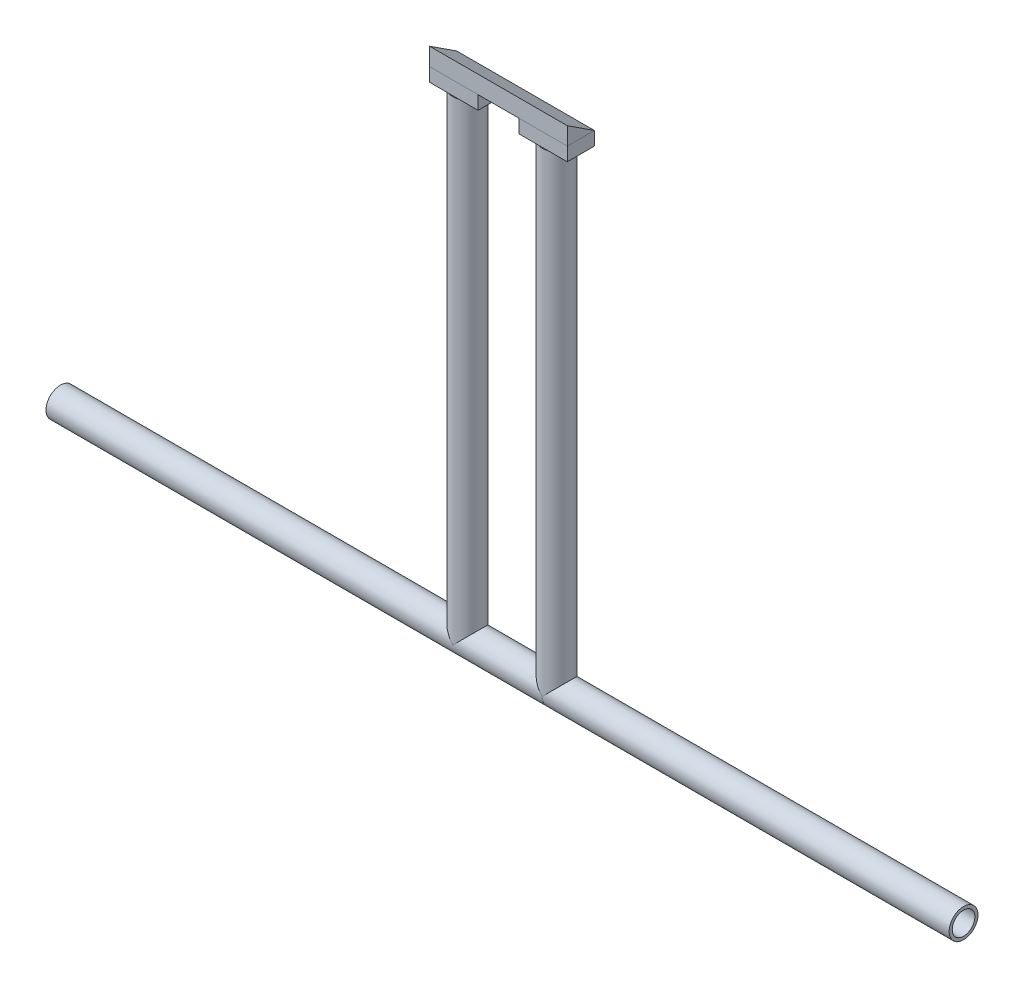
SolidWorks part; units mm, degrees
material "Hexcel AS4C (3000 Filaments)"
ref_plane "Front Plane" through (0, 0, 0) normal (0, 0, 1) x (1, 0, 0)
ref_plane "Top Plane" through (0, 0, 0) normal (0, 1, 0) x (1, 0, 0)
ref_plane "Right Plane" through (0, 0, 0) normal (1, 0, 0) x (0, 0, -1)
sketch "Sketch1" plane through (0, 0, 0) normal (0, 0, 1) x (1, 0, 0)
  line L0 (0, 350) -> (0, 0)
  line L1 (0, 0) -> (-365.75, 0)
  line L2 (0, 0) -> (300, 0)
  line L3 (-65.75, 0) -> (-65.75, 350)
  dimension "D1" = 350
  dimension "D2" = 65.75
  dimension "D3" = 300
  dimension "D4" = 300
other "Pipe - configured 21.3 X 2.3(1)"
ref_plane "Plane1" through (-65.75, 0, 0) normal (0, 1, 0) x (-1, 0, 0)
sketch "Sketch12" plane through (-65.75, 0, 0) normal (0, 1, 0) x (-1, 0, 0)
  circle A0 centre (0, 0) radius 8.35
  circle A1 centre (0, 0) radius 10.65
  point P3 (0, 10.65)
  point P5 (-10.65, 0)
  point P6 (0, -10.65)
  point P7 (10.65, 0)
  point P8 (0, 0)
  dimension "In_dia" = 16.7
  dimension "Out_dia" = 21.3
other "Pipe - configured 21.3 X 2.3(2)"
ref_plane "Plane2" through (0, 0, 0) normal (-1, 0, 0) x (0, -1, 0)
sketch "Sketch13" plane through (0, 0, 0) normal (-1, 0, 0) x (0, -1, 0)
  circle A0 centre (0, 0) radius 8.35
  circle A1 centre (0, 0) radius 10.65
  point P3 (0, 10.65)
  point P5 (-10.65, 0)
  point P6 (0, -10.65)
  point P7 (10.65, 0)
  point P8 (0, 0)
  dimension "In_dia" = 16.7
  dimension "Out_dia" = 21.3
ref_plane "Plane3" through (0, 350, 0) normal (0, 1, 0) x (1, 0, 0)
sketch "Sketch15" plane through (0, 350, 0) normal (0, 1, 0) x (1, 0, 0)
  line L1 (-83.625, 10) -> (-47.875, 10)
  line L2 (-83.625, 10) -> (-83.625, -10)
  line L3 (-83.625, -10) -> (-47.875, -10)
  line L4 (-47.875, 10) -> (-47.875, -10)
  line L5 (-83.625, 10) -> (-47.875, -10) construction
  line L6 (-83.625, -10) -> (-47.875, 10) construction
  line L7 (-17.875, 10) -> (17.875, 10)
  line L8 (-17.875, 10) -> (-17.875, -10)
  line L9 (-17.875, -10) -> (17.875, -10)
  line L10 (17.875, 10) -> (17.875, -10)
  line L11 (-17.875, 10) -> (17.875, -10) construction
  line L12 (-17.875, -10) -> (17.875, 10) construction
  point P0 (-65.75, 0)
  point P6 (0, 0)
  dimension "D1" = 35.75
  dimension "D2" = 20
  dimension "D3" = 20
  dimension "D4" = 35.75
extrude "Boss-Extrude3" add sketch "Sketch15" along normal blind 10 separate body
sketch "Sketch16" plane through (-83.625, 0, 0) normal (-1, 0, 0) x (0, 0, 1)
  line L0 (10, 360) -> (10, 373.0364)
  line L1 (-10, 360) -> (10, 360) construction
  line L2 (10, 373.0364) -> (-10, 360)
  line L3 (-10, 360) -> (-10, 350) construction
  line L4 (10, 360) -> (-10, 360)
  point P8 (9.886, 360)
extrude "Boss-Extrude4" add sketch "Sketch16" against normal up to surface (101.5 mm away) separate body up to face at (17.875, 355, 0)
